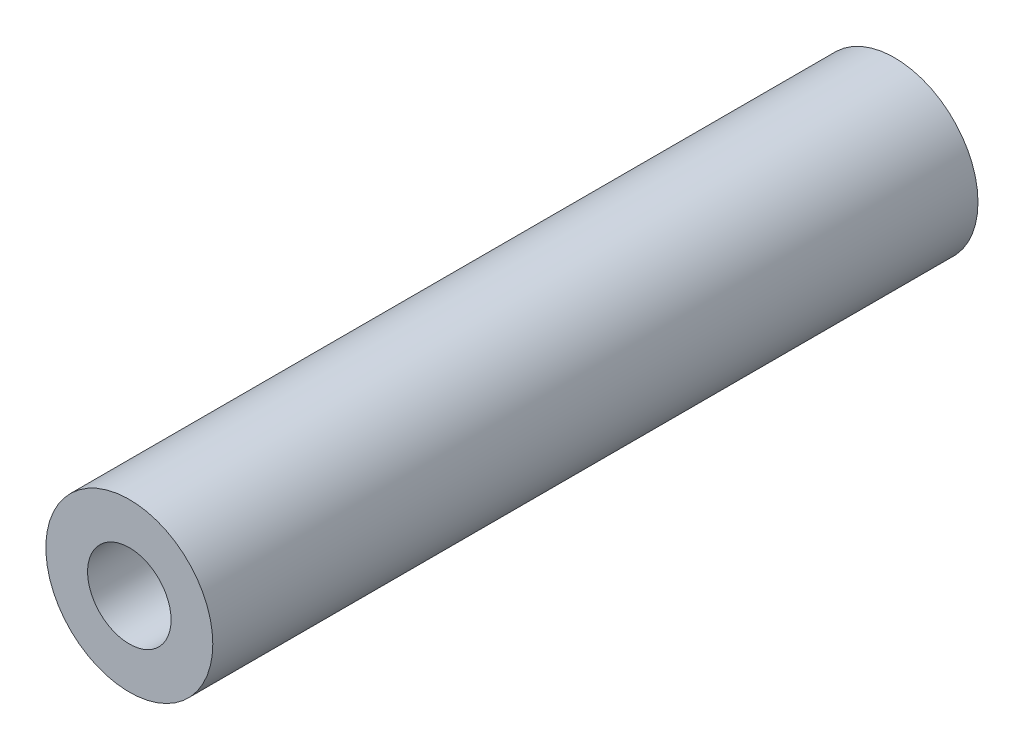
SolidWorks part; units mm, degrees
ref_plane "Front Plane" through (0, 0, 0) normal (0, 0, 1) x (1, 0, 0)
ref_plane "Top Plane" through (0, 0, 0) normal (0, 1, 0) x (1, 0, 0)
ref_plane "Right Plane" through (0, 0, 0) normal (1, 0, 0) x (0, 0, -1)
sketch "Sketch1" plane through (0, 0, 0) normal (0, 0, 1) x (1, 0, 0)
  circle A0 centre (0, 0) radius 6
  dimension "D1" = 12
extrude "Boss-Extrude1" add sketch "Sketch1" along normal blind 55
sketch "Sketch2" plane through (0, 0, 55) normal (0, 0, 1) x (1, 0, 0)
  circle A0 centre (0, 0) radius 3
  dimension "D1" = 6
extrude "Cut-Extrude1" cut sketch "Sketch2" against normal blind 14
sketch "Sketch3" plane through (0, 0, 0) normal (0, 0, -1) x (-1, 0, 0)
  circle A0 centre (0, 0) radius 3.5
  dimension "D1" = 7
extrude "Cut-Extrude2" cut sketch "Sketch3" against normal blind 14
